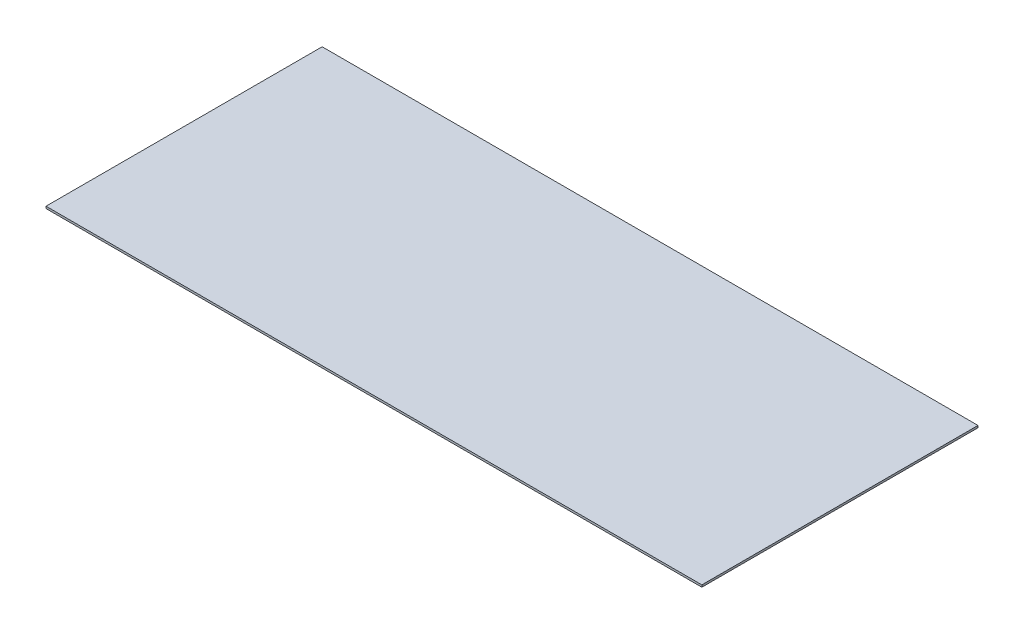
SolidWorks part; units mm, degrees
material "Фанера, сосна, ФСФ ВВ/С ГОСТ 3916.2-96"
ref_plane "Спереди" through (0, 0, 0) normal (0, 0, 1) x (1, 0, 0)
ref_plane "Сверху" through (0, 0, 0) normal (0, 1, 0) x (1, 0, 0)
ref_plane "Справа" through (0, 0, 0) normal (1, 0, 0) x (0, 0, -1)
sketch "Эскиз1" plane through (0, 0, 0) normal (0, 1, 0) x (1, 0, 0)
  line L1 (-950, -400) -> (950, -400)
  line L2 (-950, -400) -> (-950, 400)
  line L3 (-950, 400) -> (950, 400)
  line L4 (950, -400) -> (950, 400)
  line L5 (0, 400) -> (0, -400) construction
  line L6 (-950, 0) -> (950, 0) construction
  point P0 (0, 0)
  dimension "D1" = 800
  dimension "D2" = 1900
extrude "Бобышка-Вытянуть1" add sketch "Эскиз1" along normal blind 6
equation "\"длина стола\"= 1900"
equation "\"D2@Эскиз1\"=\"длина стола\""
